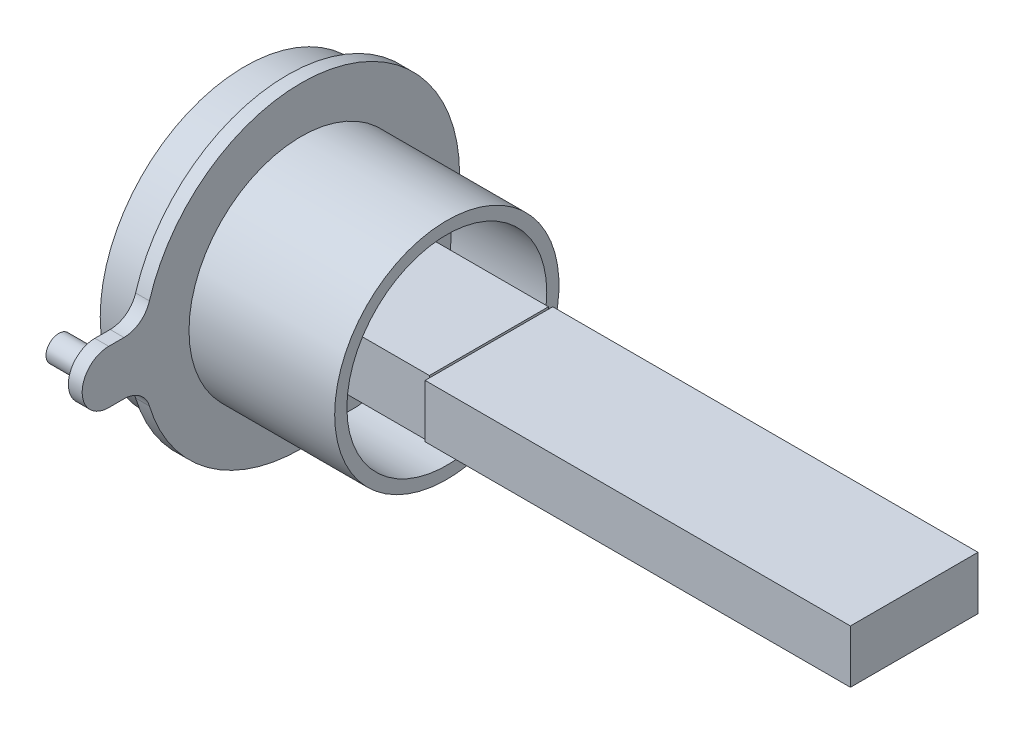
SolidWorks part; units mm, degrees
ref_plane "Front Plane" through (0, 0, 0) normal (0, 0, 1) x (1, 0, 0)
ref_plane "Top Plane" through (0, 0, 0) normal (0, 1, 0) x (1, 0, 0)
ref_plane "Right Plane" through (0, 0, 0) normal (1, 0, 0) x (0, 0, -1)
ref_plane "Plane1" through (0, 0, 0) normal (0, 0, 1) x (1, 0, 0)
sketch "Sketch1" plane through (0, 0, 0) normal (0, 0, 1) x (1, 0, 0)
  line L0 (0, 13.3985) -> (17.399, 13.3985)
  line L1 (17.399, 13.3985) -> (17.399, 11.938)
  line L2 (17.399, 11.938) -> (5.969, 11.938)
  line L3 (5.969, 11.938) -> (5.969, 0)
  line L4 (0, 13.3985) -> (0, 18.923)
  line L5 (0, 18.923) -> (-1.651, 18.923)
  line L6 (-1.651, 18.923) -> (-1.651, 17.272)
  line L7 (-1.651, 17.272) -> (-6.731, 17.272)
  line L8 (-6.731, 17.272) -> (-6.731, 11.938)
  line L9 (-6.731, 11.938) -> (3.429, 11.938)
  line L10 (3.429, 11.938) -> (3.429, 0)
  line L11 (3.429, 0) -> (5.969, 0)
  line L12 (-7.9375, 0) -> (18.6055, 0) construction
revolve "Revolve1" add sketch "Sketch1" angle 360 about L12
sketch "Sketch2" plane through (3.429, 0, 0) normal (-1, 0, 0) x (0, 0, 1)
  line L0 (-6.096, 5.334) -> (6.096, 5.334)
  line L1 (6.096, 5.334) -> (6.096, -5.334)
  line L2 (6.096, -5.334) -> (-6.096, -5.334)
  line L3 (-6.096, -5.334) -> (-6.096, 5.334)
  line L4 (0, -5.8674) -> (0, 5.8674) construction
extrude "Extrude1" add sketch "Sketch2" along normal blind 14.478
sketch "Sketch3" plane through (5.969, 0, 0) normal (1, 0, 0) x (0, 0, -1)
  line L0 (-7.112, 3.429) -> (7.112, 3.429)
  line L1 (7.112, 3.429) -> (7.112, -3.429)
  line L2 (7.112, -3.429) -> (-7.112, -3.429)
  line L3 (-7.112, -3.429) -> (-7.112, 3.429)
  line L4 (0, -3.7719) -> (0, 3.7719) construction
extrude "Extrude2" add sketch "Sketch3" along normal blind 16.4592
sketch "Sketch4" plane through (-1.651, 0, 0) normal (-1, 0, 0) x (0, 0, 1)
  line L0 (22.987, 3.175) -> (18.6547, 3.175)
  line L1 (22.987, -3.175) -> (18.6547, -3.175)
  arc A0 (18.6547, -3.175) -> (18.6547, 3.175) centre (0, 0) ccw
  arc A1 (22.987, -3.175) -> (22.987, 3.175) centre (22.987, 0) ccw
ref_plane "Plane2" through (0, 0, 0) normal (1, 0, 0) x (0, -1, 0)
extrude "Extrude3" add sketch "Sketch4" against normal up to surface (1.651 mm away) up to plane "Plane2"
fillet "Fillet1" radius 3.175 2 edges at (-0.8255, 3.175, 18.6547) (-0.8255, -3.175, 18.6547)
sketch "Sketch5" plane through (-1.651, 0, 0) normal (-1, 0, 0) x (0, 0, 1)
  circle A0 centre (22.987, 0) radius 1.524
extrude "Extrude4" add sketch "Sketch5" along normal blind 4.318
sketch "Sketch6" plane through (22.4282, 0, 0) normal (1, 0, 0) x (0, 0, -1)
  line L0 (-7.62, 3.175) -> (7.62, 3.175)
  line L1 (7.62, 3.175) -> (7.62, -3.175)
  line L2 (7.62, -3.175) -> (-7.62, -3.175)
  line L3 (-7.62, -3.175) -> (-7.62, 3.175)
extrude "Extrude5" add sketch "Sketch6" along normal blind 50.8
